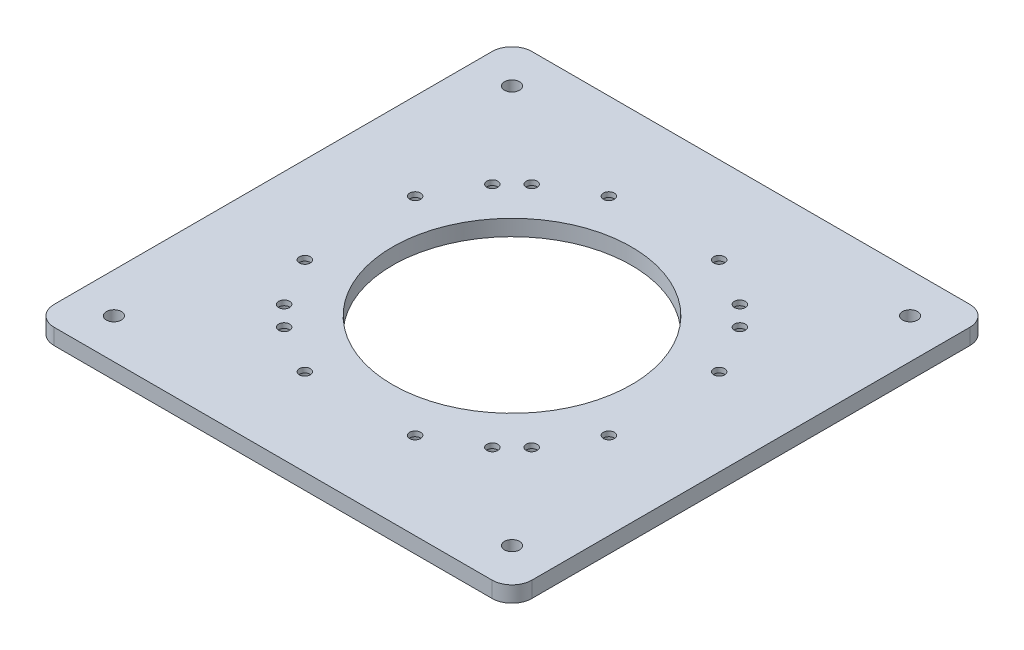
SolidWorks part; units mm, degrees
ref_plane "前视基准面" through (0, 0, 0) normal (0, 0, 1) x (1, 0, 0)
ref_plane "上视基准面" through (0, 0, 0) normal (0, 1, 0) x (1, 0, 0)
ref_plane "右视基准面" through (0, 0, 0) normal (1, 0, 0) x (0, 0, -1)
other "Configuration Table"
sketch "草图1" plane through (0, 0, 0) normal (0, 1, 0) x (1, 0, 0)
  line L0 (-160.8922, -120) -> (400.8922, -120) construction
  line L1 (0, 0) -> (240, 0)
  line L2 (0, 0) -> (0, -240)
  line L3 (0, -240) -> (240, -240)
  line L4 (240, 0) -> (240, -240)
  line L5 (120, 86.8401) -> (120, -324.1636) construction
  circle A0 centre (120, -120) radius 60
  dimension "D3" = 120
  dimension "D1" = 240
  dimension "D2" = 240
extrude "凸台-拉伸1" add sketch "草图1" along normal blind 8
sketch "草图2" plane through (0, 8, 0) normal (0, 1, 0) x (1, 0, 0)
  line L0 (0, -240) -> (240, -240) construction
  line L1 (240, -240) -> (240, 0) construction
  line L2 (240, 0) -> (0, 0) construction
  line L3 (0, 0) -> (0, -240) construction
  arc A0 (196.3802, -94.7938) -> (196.3802, -89.7938) centre (196.3802, -92.2938) ccw construction
  arc A1 (196.3802, -150.2062) -> (196.3802, -145.2062) centre (196.3802, -147.7062) ccw construction
  arc A2 (182.1844, -174.7941) -> (182.1844, -169.7941) centre (182.1844, -172.2941) ccw construction
  arc A3 (172.2941, -184.6844) -> (172.2941, -179.6844) centre (172.2941, -182.1844) ccw construction
  arc A4 (147.7062, -198.8802) -> (147.7062, -193.8802) centre (147.7062, -196.3802) ccw construction
  arc A5 (92.2938, -193.8802) -> (92.2938, -198.8802) centre (92.2938, -196.3802) ccw construction
  arc A6 (67.7059, -179.6844) -> (67.7059, -184.6844) centre (67.7059, -182.1844) ccw construction
  arc A7 (57.8156, -169.7941) -> (57.8156, -174.7941) centre (57.8156, -172.2941) ccw construction
  arc A8 (43.6198, -145.2062) -> (43.6198, -150.2062) centre (43.6198, -147.7062) ccw construction
  arc A9 (43.6198, -89.7938) -> (43.6198, -94.7938) centre (43.6198, -92.2938) ccw construction
  arc A10 (57.8156, -65.2059) -> (57.8156, -70.2059) centre (57.8156, -67.7059) ccw construction
  arc A11 (67.7059, -55.3156) -> (67.7059, -60.3156) centre (67.7059, -57.8156) ccw construction
  arc A12 (92.2938, -41.1198) -> (92.2938, -46.1198) centre (92.2938, -43.6198) ccw construction
  arc A13 (147.7062, -41.1198) -> (147.7062, -46.1198) centre (147.7062, -43.6198) ccw construction
  arc A14 (172.2941, -55.3156) -> (172.2941, -60.3156) centre (172.2941, -57.8156) ccw construction
  arc A15 (182.1844, -65.2059) -> (182.1844, -70.2059) centre (182.1844, -67.7059) ccw construction
  arc A16 (196.3802, -94.7938) -> (196.3802, -89.7938) centre (196.3802, -92.2938) ccw construction
  arc A17 (196.3802, -150.2062) -> (196.3802, -145.2062) centre (196.3802, -147.7062) ccw construction
  arc A18 (182.1844, -174.7941) -> (182.1844, -169.7941) centre (182.1844, -172.2941) ccw construction
  arc A19 (172.2941, -184.6844) -> (172.2941, -179.6844) centre (172.2941, -182.1844) ccw construction
  arc A20 (147.7062, -198.8802) -> (147.7062, -193.8802) centre (147.7062, -196.3802) ccw construction
  arc A21 (92.2938, -193.8802) -> (92.2938, -198.8802) centre (92.2938, -196.3802) ccw construction
  arc A22 (67.7059, -179.6844) -> (67.7059, -184.6844) centre (67.7059, -182.1844) ccw construction
  arc A23 (57.8156, -169.7941) -> (57.8156, -174.7941) centre (57.8156, -172.2941) ccw construction
  arc A24 (43.6198, -145.2062) -> (43.6198, -150.2062) centre (43.6198, -147.7062) ccw construction
  arc A25 (43.6198, -89.7938) -> (43.6198, -94.7938) centre (43.6198, -92.2938) ccw construction
  arc A26 (57.8156, -65.2059) -> (57.8156, -70.2059) centre (57.8156, -67.7059) ccw construction
  arc A27 (67.7059, -55.3156) -> (67.7059, -60.3156) centre (67.7059, -57.8156) ccw construction
  arc A28 (92.2938, -41.1198) -> (92.2938, -46.1198) centre (92.2938, -43.6198) ccw construction
  arc A29 (147.7062, -41.1198) -> (147.7062, -46.1198) centre (147.7062, -43.6198) ccw construction
  arc A30 (172.2941, -55.3156) -> (172.2941, -60.3156) centre (172.2941, -57.8156) ccw construction
  arc A31 (182.1844, -65.2059) -> (182.1844, -70.2059) centre (182.1844, -67.7059) ccw construction
  circle A32 centre (92.2938, -43.6198) radius 2.75
  circle A33 centre (147.7062, -43.6198) radius 2.75
  circle A34 centre (172.2941, -57.8156) radius 2.75
  circle A35 centre (182.1844, -67.7059) radius 2.75
  circle A36 centre (196.3802, -92.2938) radius 2.75
  circle A37 centre (196.3802, -147.7062) radius 2.75
  circle A38 centre (182.1844, -172.2941) radius 2.75
  circle A39 centre (172.2941, -182.1844) radius 2.75
  circle A40 centre (147.7062, -196.3802) radius 2.75
  circle A41 centre (92.2938, -196.3802) radius 2.75
  circle A42 centre (67.7059, -182.1844) radius 2.75
  circle A43 centre (57.8156, -172.2941) radius 2.75
  circle A44 centre (43.6198, -147.7062) radius 2.75
  circle A45 centre (43.6198, -92.2938) radius 2.75
  circle A46 centre (57.8156, -67.7059) radius 2.75
  circle A47 centre (67.7059, -57.8156) radius 2.75
  circle A48 centre (220, -20) radius 3.75
  circle A49 centre (20, -20) radius 3.75
  circle A50 centre (20, -220) radius 3.75
  circle A51 centre (220, -220) radius 3.75
  dimension "D1" = 5.5
  dimension "D2" = 7.5
  dimension "D3" = 20
  dimension "D4" = 20
  dimension "D5" = 20
  dimension "D6" = 20
  dimension "D7" = 20
  dimension "D8" = 20
  dimension "D9" = 20
  dimension "D10" = 20
extrude "切除-拉伸1" cut sketch "草图2" against normal blind 10
fillet "圆角1" radius 10 4 edges at (240, 4, 240) (0, 4, 240) (0, 4, 0) (240, 4, 0)
sketch "草图3" plane through (0, 0, 0) normal (0, -1, 0) x (1, 0, 0)
  circle A0 centre (147.7062, 196.3802) radius 6
  circle A1 centre (172.2941, 182.1844) radius 6
  circle A2 centre (182.1844, 172.2941) radius 6
  circle A3 centre (196.3802, 147.7062) radius 6
  circle A12 centre (196.3802, 92.2938) radius 6
  circle A13 centre (182.1844, 67.7059) radius 6
  circle A14 centre (172.2941, 57.8156) radius 6
  circle A15 centre (147.7062, 43.6198) radius 6
  circle A16 centre (92.2938, 43.6198) radius 6
  circle A17 centre (67.7059, 57.8156) radius 6
  circle A18 centre (57.8156, 67.7059) radius 6
  circle A19 centre (43.6198, 92.2938) radius 6
  circle A20 centre (43.6198, 147.7062) radius 6
  circle A21 centre (57.8156, 172.2941) radius 6
  circle A22 centre (67.7059, 182.1844) radius 6
  circle A23 centre (92.2938, 196.3802) radius 6
  dimension "D1" = 12
extrude "切除-拉伸2" cut sketch "草图3" against normal blind 5.5
